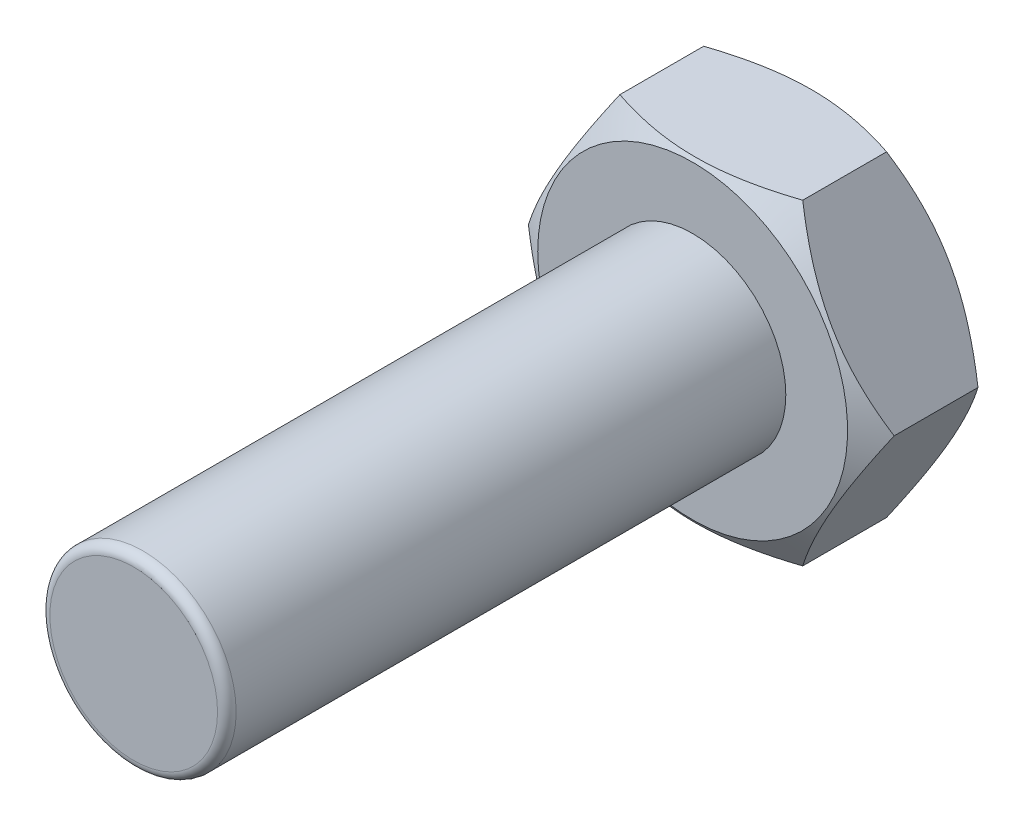
SolidWorks part; units mm, degrees
material "1.0036 (S235JRG1)"
ref_plane "Ön Düzlem" through (0, 0, 0) normal (0, 0, 1) x (1, 0, 0)
ref_plane "Üst Düzlem" through (0, 0, 0) normal (0, 1, 0) x (1, 0, 0)
ref_plane "Sağ Düzlem" through (0, 0, 0) normal (1, 0, 0) x (0, 0, -1)
sketch "Çizim1" plane through (0, 0, 0) normal (0, 0, 1) x (1, 0, 0)
  line L1 (9.815, 0) -> (4.9075, 8.5)
  line L2 (4.9075, 8.5) -> (-4.9075, 8.5)
  line L3 (-4.9075, 8.5) -> (-9.815, 0)
  line L4 (-9.815, 0) -> (-4.9075, -8.5)
  line L5 (-4.9075, -8.5) -> (4.9075, -8.5)
  line L6 (4.9075, -8.5) -> (9.815, 0)
  circle A0 centre (0, 0) radius 8.5 construction
  dimension "D1" = 17
extrude "Yükseklik-Ekstrüzyon1" add sketch "Çizim1" along normal blind 6.5
sketch "Çizim2" plane through (0, 0, 6.5) normal (0, 0, 1) x (1, 0, 0)
  circle A0 centre (0, 0) radius 5
  dimension "D1" = 10
extrude "Yükseklik-Ekstrüzyon2" add sketch "Çizim2" along normal blind 30
cosmetic thread "Kozmetik Diş Açma1" parameters "D2"=8.344
sketch "Çizim3" plane through (0, 0, 0) normal (0, 1, 0) x (1, 0, 0)
  line L0 (-9.815, 0) -> (-8.315, 0)
  line L1 (-4.9075, 0) -> (-9.815, 0) construction
  line L2 (-8.315, 0) -> (-9.815, -1)
  line L3 (-9.815, -6.5) -> (-9.815, 0) construction
  line L4 (-9.815, -1) -> (-9.815, 0)
  line L9 (-9.815, -6.5) -> (-9.815, -5.5)
  line L10 (-9.815, -5.5) -> (-8.315, -6.5)
  line L11 (-4.9075, -6.5) -> (-9.815, -6.5) construction
  line L12 (-8.315, -6.5) -> (-9.815, -6.5)
  line L13 (0, 0) -> (0, -6.5) construction
  line L14 (-5, -6.5) -> (5, -6.5) construction
  dimension "D1" = 1.5
  dimension "D2" = 1
  dimension "D3" = 1
  dimension "D4" = 1.5
revolve "Kes-Döndür1" cut sketch "Çizim3" angle 360 about L13
fillet "Radyus1" radius 0.5 1 edges at (5, 0, 36.5)
